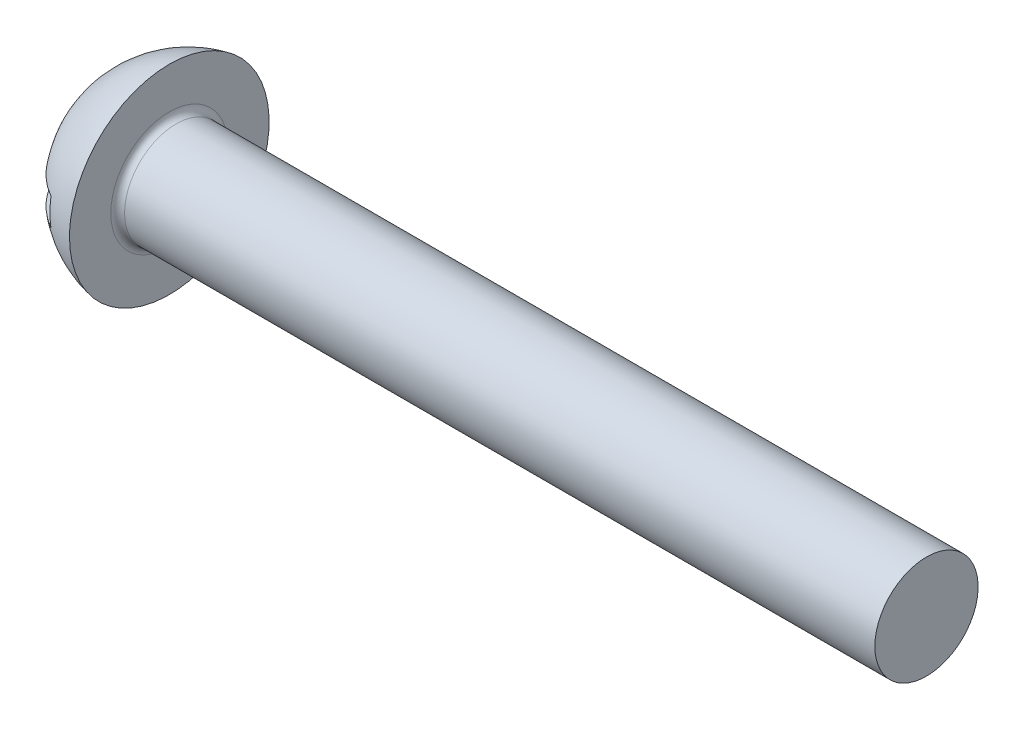
SolidWorks part; units mm, degrees
ref_plane "前视基准面" through (0, 0, 0) normal (0, 0, 1) x (1, 0, 0)
ref_plane "上视基准面" through (0, 0, 0) normal (0, 1, 0) x (1, 0, 0)
ref_plane "右视基准面" through (0, 0, 0) normal (1, 0, 0) x (0, 0, -1)
sketch "草图1" plane through (0, 0, 0) normal (0, 0, 1) x (1, 0, 0)
  line L0 (0, 0) -> (1.5, 0) construction
  line L1 (2.4, 2.9) -> (2.4, 1.5)
  line L2 (2.4, 1.5) -> (10.4, 1.5)
  line L3 (10.4, 1.5) -> (24.4, 1.5)
  line L4 (24.4, 1.5) -> (24.4, 0)
  line L5 (24.4, 0) -> (0, 0)
  line L6 (1.5, 0.4) -> (1.5, -0.4) construction
  line L7 (24.4, 0) -> (24.6, 0) construction
  arc A0 (0, 0) -> (2.4, 2.9) centre (2.9521, 0) cw
  dimension "k" = 2.4
  dimension "l" = 22
  dimension "d" = 3
  dimension "dk" = 5.8
  dimension "l0" = 14
  dimension "n" = 0.8
  dimension "t" = 1.5
  dimension "r" = 0.2
revolve "旋转1" add sketch "草图1" angle 360 about L0
cosmetic thread "装饰螺纹线1" parameters "D1"=14, "D2"=2.598
sketch "草图2" plane through (0, 0, 0) normal (1, 0, 0) x (0, 0, -1)
  line L0 (2.9, 0.4) -> (-2.9, 0.4)
  line L1 (-2.9, 0.4) -> (-2.9, -0.4)
  line L2 (-2.9, -0.4) -> (2.9, -0.4)
  line L3 (2.9, -0.4) -> (2.9, 0.4)
  circle A1 centre (0, 0) radius 2.9 construction
extrude "切除-拉伸1" cut sketch "草图2" along normal up to vertex (1.5 mm away) up to point (1.5, 0.4, 0)
fillet "圆角1" radius 0.2 1 edges at (2.4, 0, 1.5)
equation "\"D2@装饰螺纹线1\" = \"d@草图1\"*0.866"
equation "\"D1@装饰螺纹线1\" =\"l0@草图1\""
equation "\"D1@圆角1\" = \"r@草图1\""
